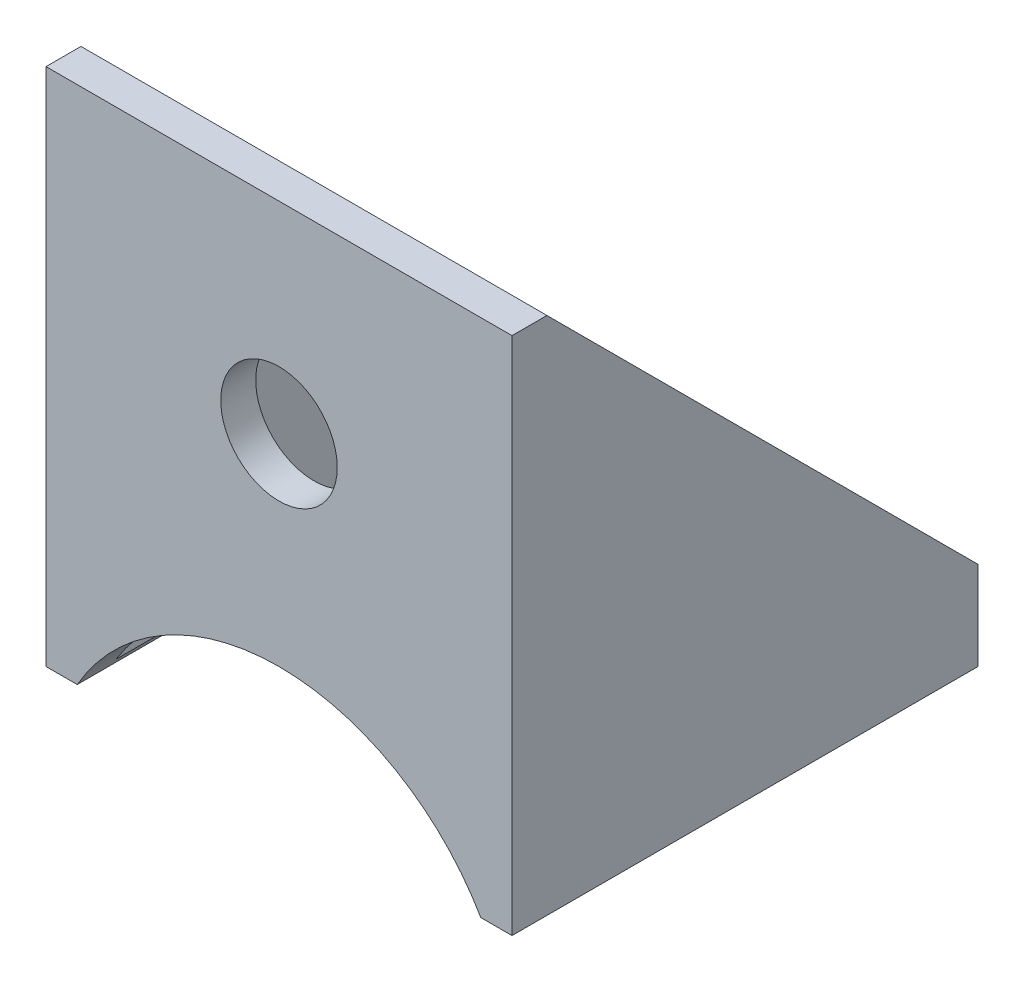
SolidWorks part; units mm, degrees
ref_plane "Front Plane" through (0, 0, 0) normal (0, 0, 1) x (1, 0, 0)
ref_plane "Top Plane" through (0, 0, 0) normal (0, 1, 0) x (1, 0, 0)
ref_plane "Right Plane" through (0, 0, 0) normal (1, 0, 0) x (0, 0, -1)
sketch "Sketch1" plane through (0, 0, 0) normal (0, 1, 0) x (1, 0, 0)
  line L0 (-12.7, 12.7) -> (-12.7, -12.7)
  line L1 (-12.7, -12.7) -> (12.7, -12.7)
  line L2 (12.7, -12.7) -> (12.7, 12.7)
  line L3 (12.7, 12.7) -> (10.795, 12.7)
  line L4 (10.795, 12.7) -> (10.795, -10.795)
  line L5 (10.795, -10.795) -> (-10.795, -10.795)
  line L6 (-10.795, -10.795) -> (-10.795, 12.7)
  line L7 (-10.795, 12.7) -> (-12.7, 12.7)
  point P2 (-10.3251, 8.7043)
  point P9 (12.3195, 12.3069)
  point P10 (-12.7, 0)
  point P12 (0, -10.795)
  dimension "D1" = 1.905
  dimension "D2" = 1.905
  dimension "D3" = 1.905
  dimension "D4" = 25.4
  dimension "D5" = 25.4
extrude "Boss-Extrude1" add sketch "Sketch1" along normal blind 34.671
sketch "Sketch2" plane through (-12.7, 0, 0) normal (-1, 0, 0) x (0, 0, 1)
  line L0 (-12.7, 11.176) -> (10.795, 34.671)
  line L1 (-12.7, 34.671) -> (12.7, 34.671) construction
  line L2 (12.7, 34.671) -> (12.7, 0) construction
  line L3 (10.795, 34.671) -> (-12.7, 34.671)
  line L6 (-12.7, 34.671) -> (-12.7, 11.176)
  point P3 (0, 0)
  dimension "D1" = 1.905
  dimension "D2" = 45
extrude "Cut-Extrude1" cut sketch "Sketch2" against normal through all
sketch "Sketch3" plane through (0, 0, 12.7) normal (0, 0, 1) x (1, 0, 0)
  line L1 (-12.7, 12.7) -> (12.7, 12.7) construction
  line L2 (-12.7, 34.671) -> (-12.7, 0) construction
  line L3 (12.7, 34.671) -> (12.7, 0) construction
  line L4 (-12.7, 34.671) -> (12.7, 34.671) construction
  circle A0 centre (0, 23.6855) radius 3.175
  point P5 (0, 0)
  point P8 (0, 0)
  dimension "D1" = 6.35
  dimension "D2" = 21.971
  dimension "D3" = 10.9855
extrude "Cut-Extrude2" cut sketch "Sketch3" against normal through all
sketch "Sketch4" plane through (0, 0, 12.7) normal (0, 0, 1) x (1, 0, 0)
  line L0 (-12.7, 0) -> (12.7, 0) construction
  line L1 (-12.7, 0) -> (12.7, 0)
  line L2 (-10.9985, 6.35) -> (-12.7, 6.35)
  line L3 (-12.7, 34.671) -> (-12.7, 0) construction
  line L4 (-12.7, 6.35) -> (-12.7, 0)
  line L5 (10.9985, 6.35) -> (12.7, 6.35)
  line L6 (12.7, 34.671) -> (12.7, 0) construction
  line L7 (12.7, 6.35) -> (12.7, 0)
  arc A0 (10.9985, 6.35) -> (-10.9985, 6.35) centre (0, 0) ccw
  dimension "D1" = 6.35
extrude "Cut-Extrude3" cut sketch "Sketch4" against normal through all
